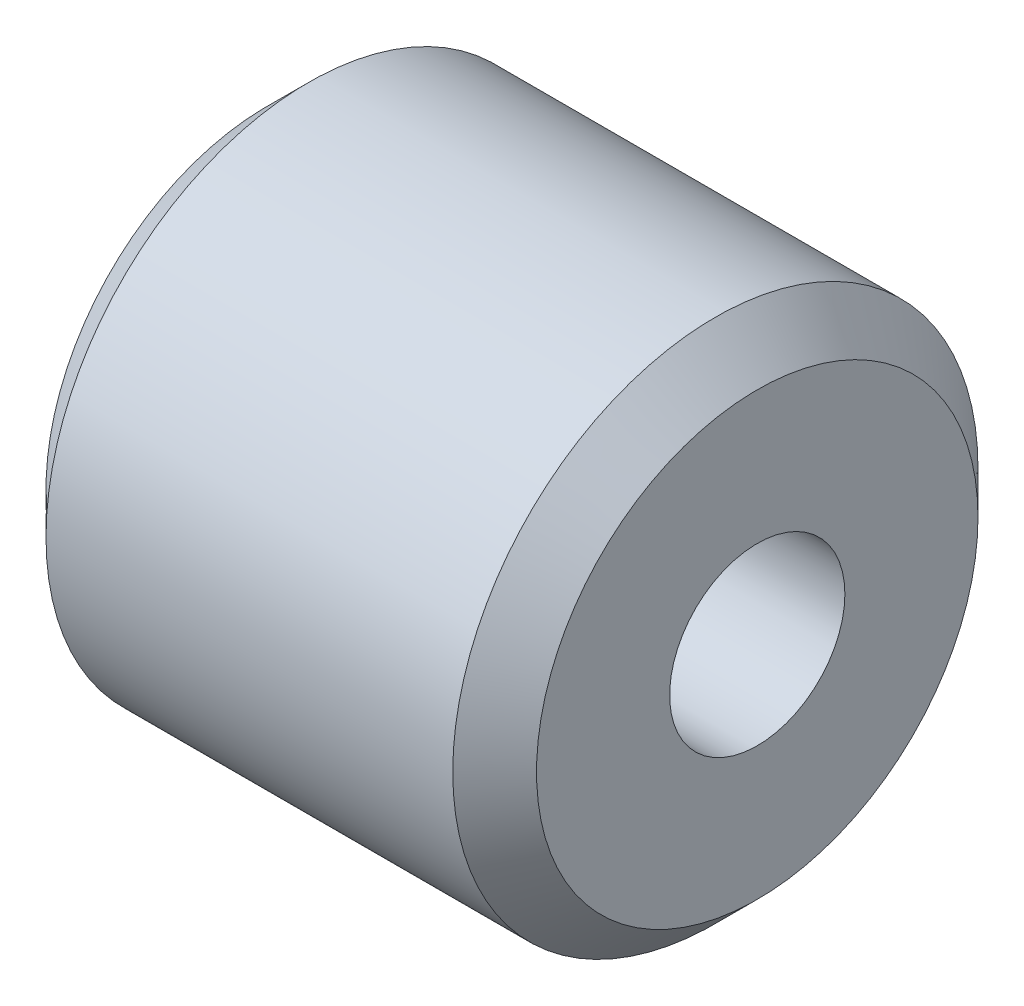
SolidWorks part; units mm, degrees
ref_plane "Front Plane" through (0, 0, 0) normal (0, 0, 1) x (1, 0, 0)
ref_plane "Top Plane" through (0, 0, 0) normal (0, 1, 0) x (1, 0, 0)
ref_plane "Right Plane" through (0, 0, 0) normal (1, 0, 0) x (0, 0, -1)
sketch "Sketch1" plane through (0, 0, 0) normal (1, 0, 0) x (0, 0, -1)
  circle A0 centre (0, 0) radius 1.59
  circle A1 centre (0, 0) radius 4.765
  dimension "D1" = 3.18
  dimension "D2" = 9.53
extrude "Boss-Extrude1" add sketch "Sketch1" along normal mid plane 8.9
chamfer "Chamfer1" distance 0.76 angle 45 2 edges at (4.45, 0, -4.765) (-4.45, 0, -4.765)
